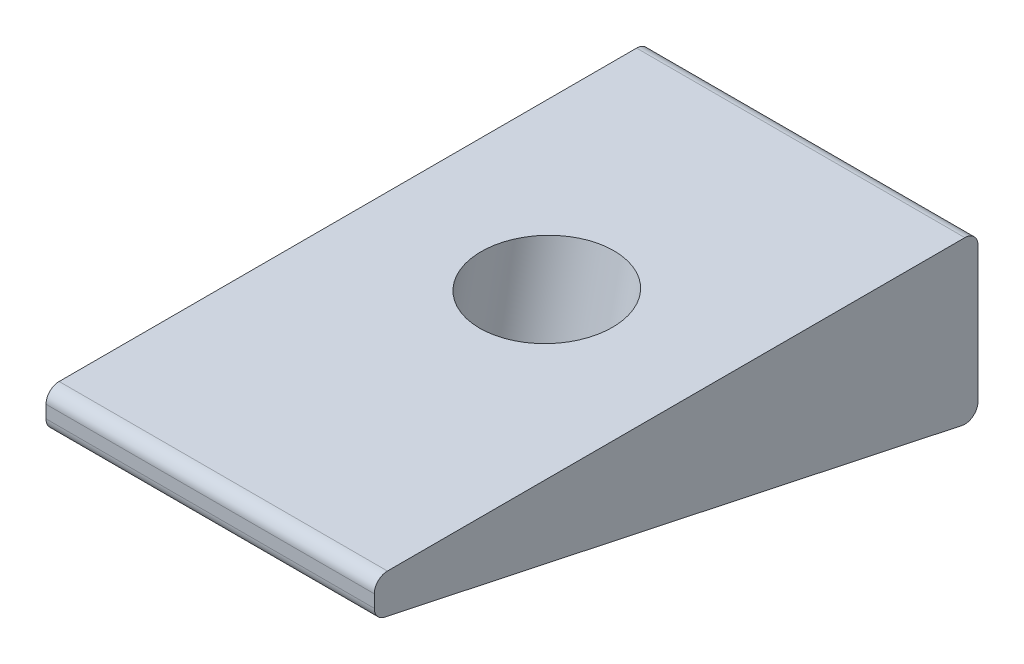
SolidWorks part; units mm, degrees
ref_plane "Front Plane" through (0, 0, 0) normal (0, 0, 1) x (1, 0, 0)
ref_plane "Top Plane" through (0, 0, 0) normal (0, 1, 0) x (1, 0, 0)
ref_plane "Right Plane" through (0, 0, 0) normal (1, 0, 0) x (0, 0, -1)
sketch "Sketch1" plane through (0, 0, 0) normal (1, 0, 0) x (0, 0, -1)
  line L0 (0, 0) -> (-45.9729, 0)
  line L2 (0, -25) -> (0, 0)
  line L3 (0, -25) -> (-45.9729, -15.2282)
  line L4 (-45.9729, -15.2282) -> (-45.9729, 0)
  dimension "D1" = 47
  dimension "D2" = 25
  dimension "D3" = 78
extrude "Boss-Extrude1" add sketch "Sketch1" along normal blind 25
sketch "Sketch2" plane through (0, -23.9193, 5.0842) normal (0, -0.9781, 0.2079) x (1, 0, 0)
  line L0 (25, -5.1978) -> (0, -5.1978) construction
  circle A0 centre (12.5, 17.3022) radius 5
  dimension "D1" = 10
  dimension "D2" = 22.5
extrude "Cut-Extrude1" cut sketch "Sketch2" against normal blind 25
sketch "Sketch3" plane through (0, 0, 0) normal (-1, 0, 0) x (0, 0, 1)
  line L0 (45.9729, 0) -> (45.9729, -15.2282) construction
  line L1 (0, 0) -> (45.9729, 0)
  line L2 (0, 0) -> (0, -12.4581)
  line L3 (0, -12.4581) -> (45.9729, -12.4581)
  line L4 (45.9729, 0) -> (45.9729, -12.4581)
extrude "Cut-Extrude2" cut sketch "Sketch3" against normal through all
fillet "Fillet1" radius 1 4 edges at (12.5, -15.2282, 45.9729) (12.5, -25, 0) (12.5, -12.4581, 45.9729) (12.5, -12.4581, 0)
